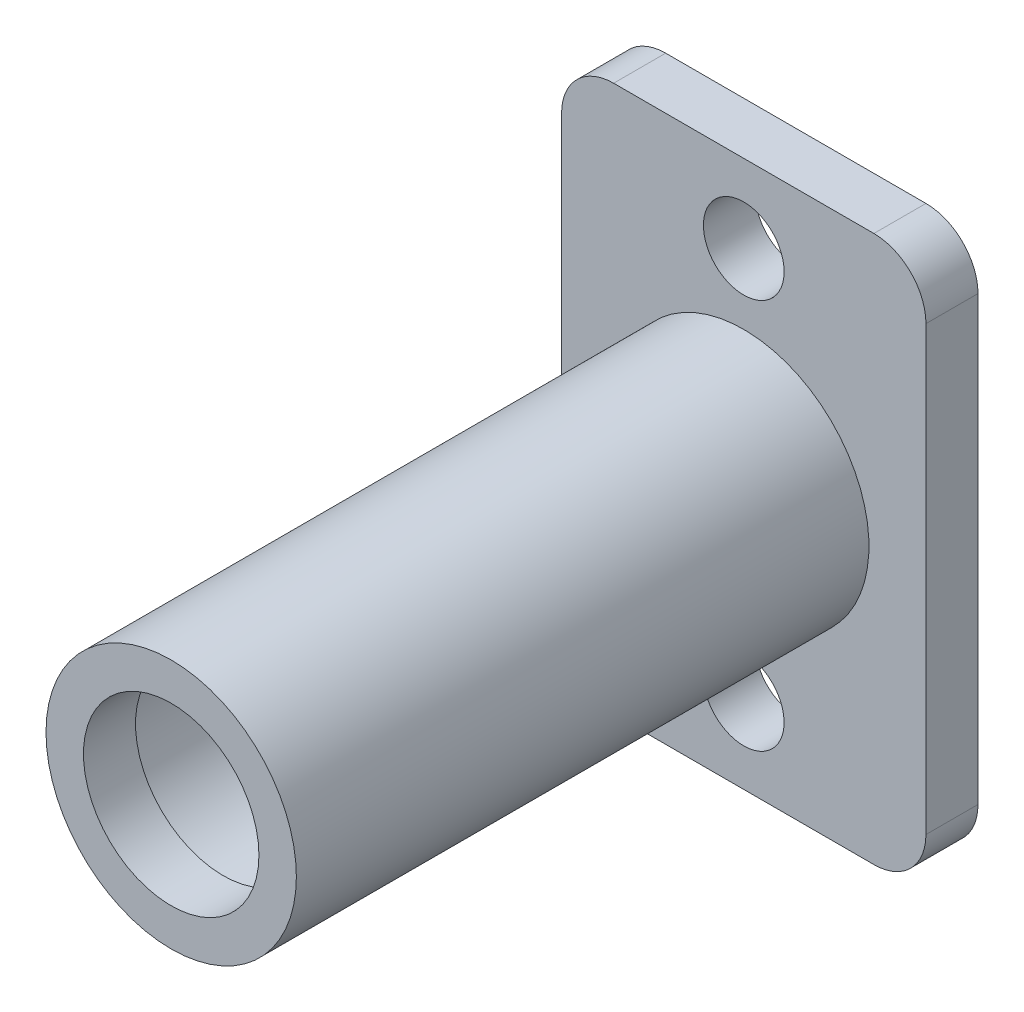
SolidWorks part; units mm, degrees
ref_plane "Front Plane" through (0, 0, 0) normal (0, 0, 1) x (1, 0, 0)
ref_plane "Top Plane" through (0, 0, 0) normal (0, 1, 0) x (1, 0, 0)
ref_plane "Right Plane" through (0, 0, 0) normal (1, 0, 0) x (0, 0, -1)
sketch "Sketch1" plane through (0, 0, 0) normal (0, 0, 1) x (1, 0, 0)
  line L0 (-7, 0) -> (7, 0) construction
  line L1 (-7, -10.5) -> (7, -10.5)
  line L2 (-7, -10.5) -> (-7, 10.5)
  line L3 (-7, 10.5) -> (7, 10.5)
  line L4 (7, -10.5) -> (7, 10.5)
  line L5 (-7, -10.5) -> (7, 10.5) construction
  line L6 (-7, 10.5) -> (7, -10.5) construction
  circle A0 centre (0, 7.5) radius 1.55
  circle A1 centre (0, -7.5) radius 1.55
  circle A2 centre (0, 0) radius 3.81
  point P0 (0, 0)
  dimension "D3" = 3.1
  dimension "D4" = 7.62
  dimension "D1" = 21
  dimension "D2" = 14
  dimension "D5" = 7.5
extrude "Boss-Extrude1" add sketch "Sketch1" along normal blind 2
fillet "Fillet1" radius 2 4 edges at (-7, 10.5, 1) (-7, -10.5, 1) (7, -10.5, 1) (7, 10.5, 1)
sketch "Sketch3" plane through (0, 0, 2) normal (0, 0, 1) x (1, 0, 0)
  circle A0 centre (0, 0) radius 3.81
  circle A1 centre (0, 0) radius 4.81
  dimension "D1" = 7.62
  dimension "D2" = 1
extrude "Boss-Extrude2" add sketch "Sketch3" along normal blind 20
sketch "Sketch4" plane through (0, 0, 22) normal (0, 0, 1) x (1, 0, 0)
  circle A0 centre (0, 0) radius 4.81
  circle A1 centre (0, 0) radius 3.3712
extrude "Boss-Extrude3" add sketch "Sketch4" along normal blind 2
